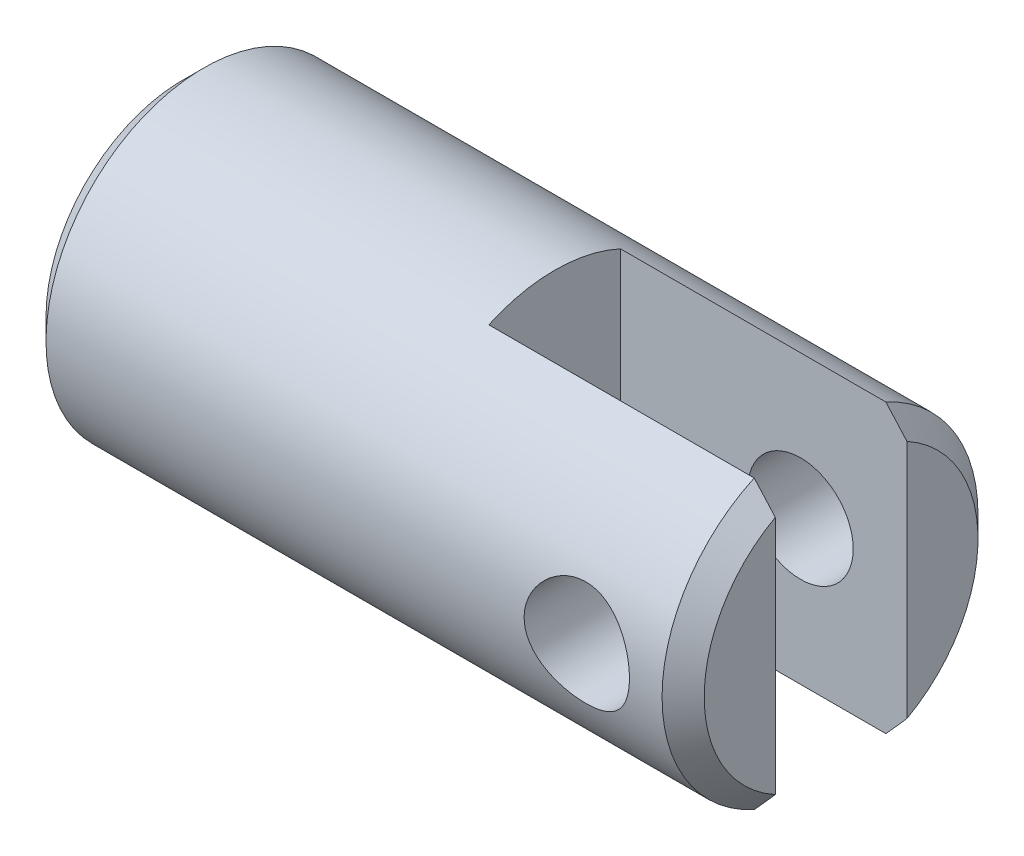
SolidWorks part; units mm, degrees
ref_plane "Front" through (0, 0, 0) normal (0, 0, 1) x (1, 0, 0)
ref_plane "Top" through (0, 0, 0) normal (0, 1, 0) x (1, 0, 0)
ref_plane "Right" through (0, 0, 0) normal (1, 0, 0) x (0, 0, -1)
sketch "Sketch1" plane through (0, 0, 0) normal (1, 0, 0) x (0, 0, -1)
  circle A0 centre (0, 0) radius 9.525
  dimension "D1" = 19.05
extrude "Base-Extrude" add sketch "Sketch1" along normal blind 39.6875
sketch "Sketch2" plane through (39.6875, 0, 0) normal (1, 0, 0) x (0, 0, -1)
  line L0 (0, 0) -> (0, 11.9045) construction
  line L1 (-3.9688, 8.6588) -> (-3.9688, -8.6588)
  line L3 (3.9688, -8.6588) -> (3.9688, 8.6588)
  arc A0 (3.9688, 8.6588) -> (-3.9688, 8.6588) centre (0, 0) ccw
  circle A1 centre (0, 0) radius 9.525
  arc A2 (-3.9688, -8.6588) -> (3.9688, -8.6588) centre (0, 0) ccw
  dimension "D2" = 7.9375
  dimension "D1" = 0
extrude "Cut-Extrude1" cut sketch "Sketch2" against normal blind 17.272
sketch "Sketch3" plane through (0, 0, 0) normal (0, 0, 1) x (1, 0, 0)
  line L0 (39.6875, 0) -> (22.4155, 0) construction
  line L1 (0, 0) -> (33.274, 0) construction
  circle A0 centre (33.274, 0) radius 3.175
  dimension "D1" = 6.35
  dimension "D2" = 33.274
extrude "Cut-Extrude2" cut sketch "Sketch3" against normal through all and the other way through all
chamfer "Chamfer1" distance 1.27 angle 45 3 edges at (0, 0, -9.525) (39.6875, 0, 9.525) (39.6875, 0, -9.525)
sketch "Sketch4" plane through (0, 0, 0) normal (-1, 0, 0) x (0, 0, 1)
  circle A0 centre (0, 0) radius 3.175
  dimension "D1" = 6.35
extrude "Cut-Extrude3" [suppressed] cut sketch "Sketch4" against normal blind 19.05
